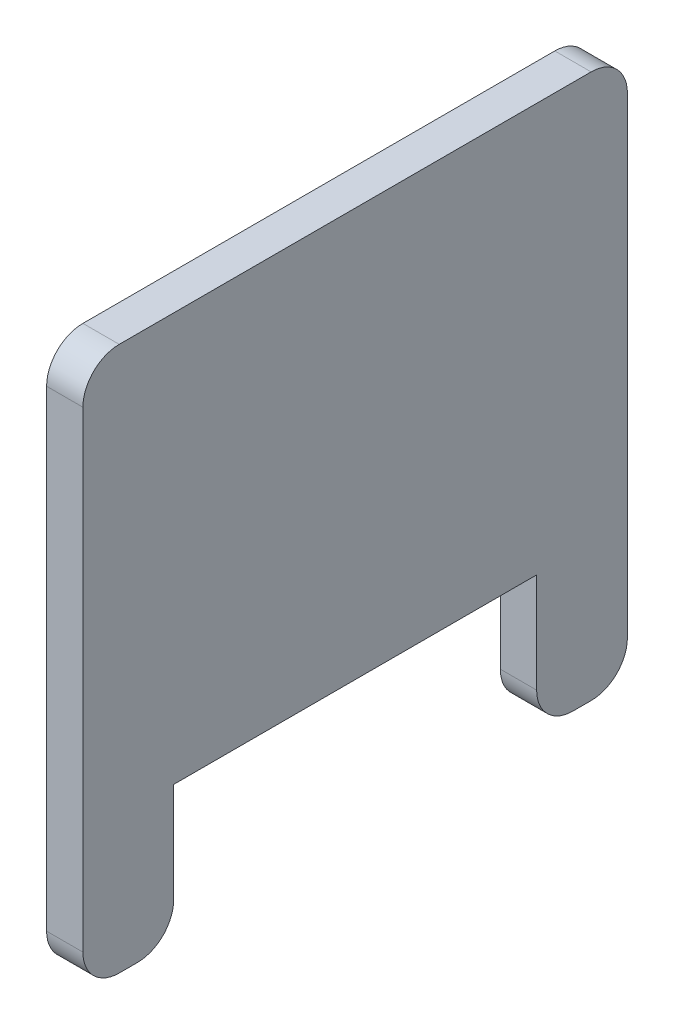
SolidWorks part; units mm, degrees
ref_plane "Front Plane" through (0, 0, 0) normal (0, 0, 1) x (1, 0, 0)
ref_plane "Top Plane" through (0, 0, 0) normal (0, 1, 0) x (1, 0, 0)
ref_plane "Right Plane" through (0, 0, 0) normal (1, 0, 0) x (0, 0, -1)
sketch "Sketch10" plane through (0, 0, 0) normal (1, 0, 0) x (0, 0, -1)
  line L1 (150, 187.5) -> (0, 187.5)
  line L2 (150, 187.5) -> (150, 37.5)
  line L3 (150, 37.5) -> (0, 37.5)
  line L4 (0, 187.5) -> (0, 37.5)
  line L5 (150, 187.5) -> (0, 37.5) construction
  line L6 (150, 37.5) -> (0, 187.5) construction
  point P0 (75, 112.5)
  dimension "D1" = 150
  dimension "D2" = 150
extrude "Boss-Extrude3" add sketch "Sketch10" along normal blind 10
sketch "Sketch12" plane through (0, 0, 0) normal (-1, 0, 0) x (0, 0, 1)
  line L0 (0, 37.5) -> (-150, 37.5) construction
  line L1 (-125, 37.5) -> (-25, 37.5)
  line L2 (-125, 37.5) -> (-125, 75)
  line L3 (-125, 75) -> (-25, 75)
  line L4 (-25, 37.5) -> (-25, 75)
  dimension "D1" = 25
  dimension "D2" = 25
extrude "Cut-Extrude2" cut sketch "Sketch12" against normal blind 10
fillet "Fillet7" radius 10 6 edges at (5, 37.5, -150) (5, 37.5, -125) (5, 37.5, -25) (5, 37.5, 0) (5, 187.5, -150) (5, 187.5, 0)
